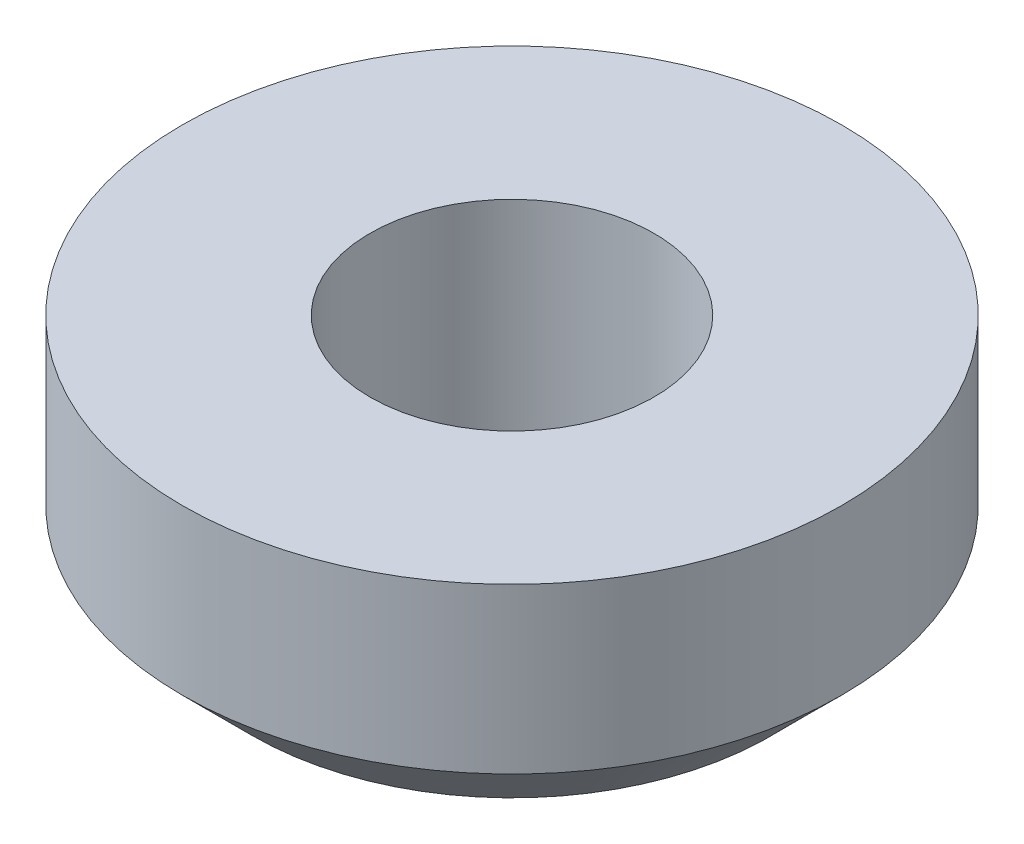
SolidWorks part; units mm, degrees
ref_plane "Front Plane" through (0, 0, 0) normal (0, 0, 1) x (1, 0, 0)
ref_plane "Top Plane" through (0, 0, 0) normal (0, 1, 0) x (1, 0, 0)
ref_plane "Right Plane" through (0, 0, 0) normal (1, 0, 0) x (0, 0, -1)
sketch "Sketch1" plane through (0, 0, 0) normal (0, 1, 0) x (1, 0, 0)
  circle A0 centre (0, 0) radius 3.025
  circle A1 centre (0, 0) radius 7.025
  dimension "D1" = 4
  dimension "D2" = 6.05
extrude "Boss-Extrude1" add sketch "Sketch1" along normal blind 5
chamfer "Chamfer1" distance 1.5 angle 45 1 edges at (0, 0, 7.025)
